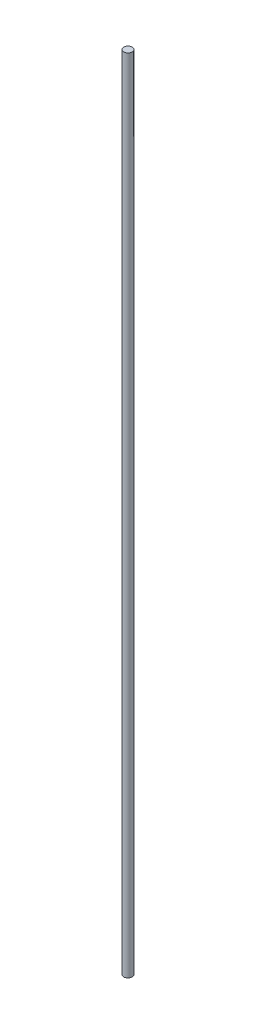
SolidWorks part; units mm, degrees
ref_plane "Front Plane" through (0, 0, 0) normal (0, 0, 1) x (1, 0, 0)
ref_plane "Top Plane" through (0, 0, 0) normal (0, 1, 0) x (1, 0, 0)
ref_plane "Right Plane" through (0, 0, 0) normal (1, 0, 0) x (0, 0, -1)
sketch "Sketch1" plane through (0, 0, 0) normal (0, 1, 0) x (1, 0, 0)
  circle A0 centre (0, 0) radius 3.1
  dimension "D1" = 6.2
extrude "Boss-Extrude1" add sketch "Sketch1" along normal blind 580
